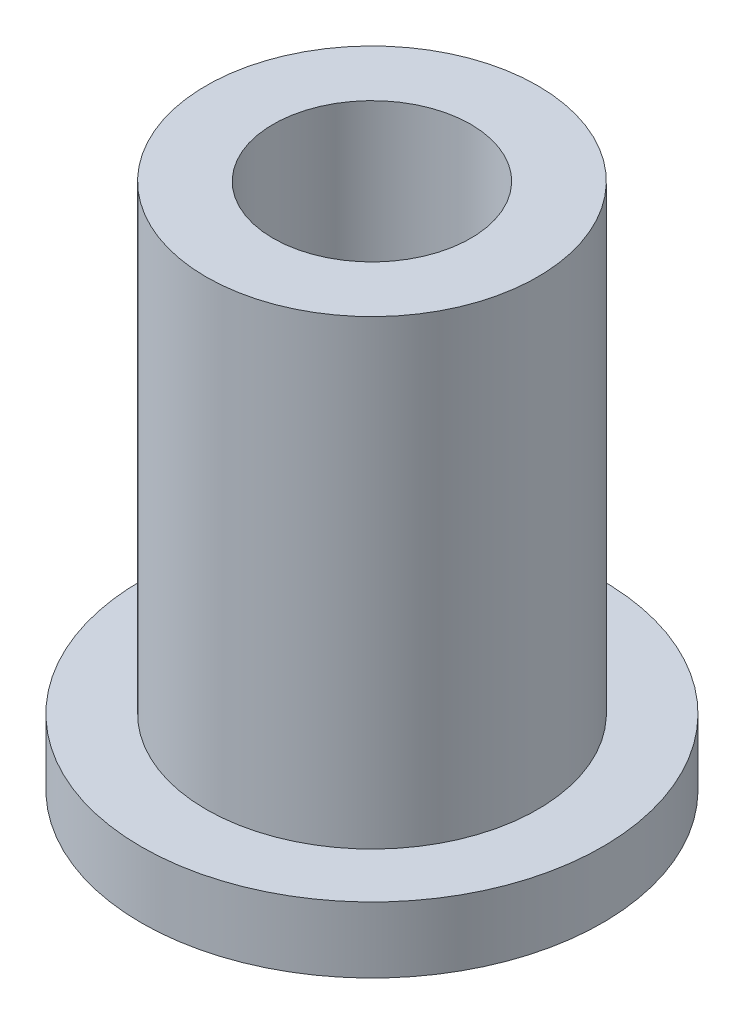
SolidWorks part; units mm, degrees
material "6061 Alloy"
ref_plane "Front Plane" through (0, 0, 0) normal (0, 0, 1) x (1, 0, 0)
ref_plane "Top Plane" through (0, 0, 0) normal (0, 1, 0) x (1, 0, 0)
ref_plane "Right Plane" through (0, 0, 0) normal (1, 0, 0) x (0, 0, -1)
sketch "Sketch1" plane through (0, 0, 0) normal (0, 1, 0) x (1, 0, 0)
  circle A0 centre (0, 0) radius 5.5562
  dimension "D1" = 11.1125
extrude "Boss-Extrude1" add sketch "Sketch1" along normal blind 1.5875
sketch "Sketch2" plane through (0, 1.5875, 0) normal (0, 1, 0) x (1, 0, 0)
  circle A1 centre (0, 0) radius 3.9942
  dimension "D2" = 7.9883
extrude "Boss-Extrude2" add sketch "Sketch2" along normal blind 11.1125
sketch "Sketch3" plane through (0, 12.7, 0) normal (0, 1, 0) x (1, 0, 0)
  circle A0 centre (0, 0) radius 2.3813
  dimension "D1" = 4.7625
extrude "Cut-Extrude1" cut sketch "Sketch3" against normal up to surface (12.7 mm away) contours A0 up to face at (0, 0, 5.5562)
equation "\"D1@Boss-Extrude2\"=1/2-1/16"
